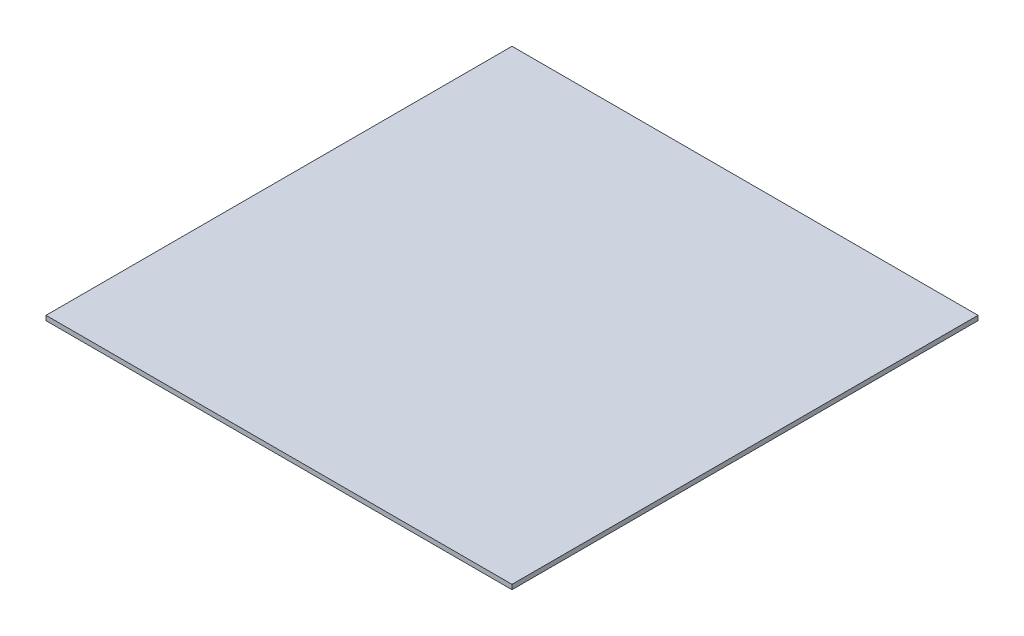
SolidWorks part; units mm, degrees
ref_plane "Front Plane" through (0, 0, 0) normal (0, 0, 1) x (1, 0, 0)
ref_plane "Top Plane" through (0, 0, 0) normal (0, 1, 0) x (1, 0, 0)
ref_plane "Right Plane" through (0, 0, 0) normal (1, 0, 0) x (0, 0, -1)
sketch "Sketch1" plane through (0, 0, 0) normal (0, 1, 0) x (1, 0, 0)
  line L1 (-100, -100) -> (100, -100)
  line L2 (-100, -100) -> (-100, 100)
  line L3 (-100, 100) -> (100, 100)
  line L4 (100, -100) -> (100, 100)
  line L5 (-100, -100) -> (100, 100) construction
  line L6 (-100, 100) -> (100, -100) construction
  point P0 (0, 0)
  dimension "D1" = 200
extrude "Boss-Extrude1" add sketch "Sketch1" along normal blind 2
